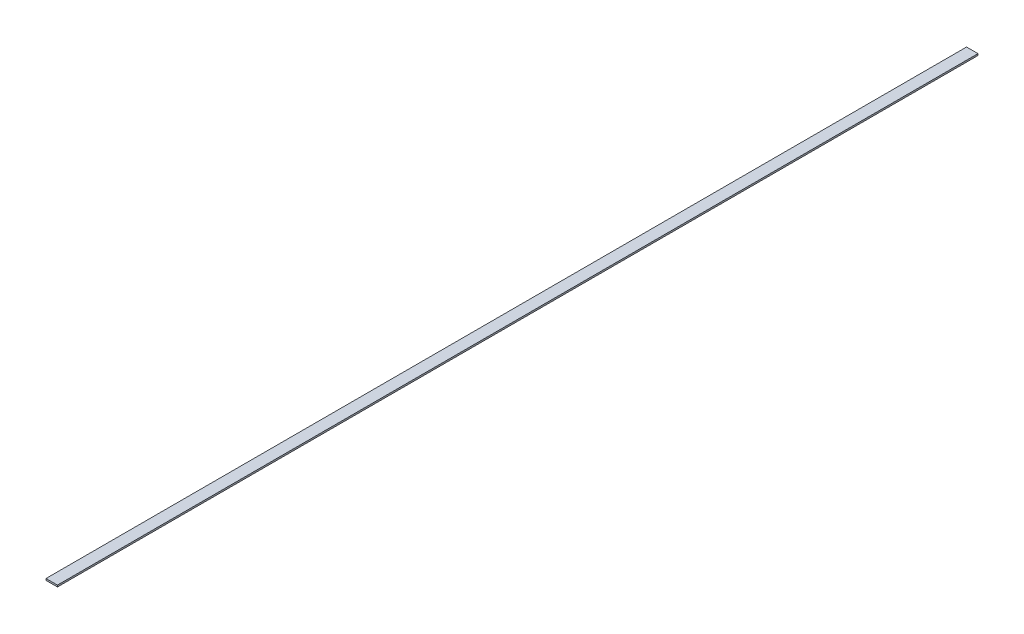
SolidWorks part; units mm, degrees
material "Manual Density from Real Component Bordo attacco e uscita"
ref_plane "Piano frontale" through (0, 0, 0) normal (0, 0, 1) x (1, 0, 0)
ref_plane "Piano superiore" through (0, 0, 0) normal (0, 1, 0) x (1, 0, 0)
ref_plane "Piano destro" through (0, 0, 0) normal (1, 0, 0) x (0, 0, -1)
sketch "Schizzo1" plane through (0, 0, 0) normal (0, 0, 1) x (1, 0, 0)
  line L1 (4.1, -0.6) -> (-4.1, -0.6)
  line L2 (4.1, -0.6) -> (4.1, 0.6)
  line L3 (4.1, 0.6) -> (-4.1, 0.6)
  line L4 (-4.1, -0.6) -> (-4.1, 0.6)
  line L5 (4.1, -0.6) -> (-4.1, 0.6) construction
  line L6 (4.1, 0.6) -> (-4.1, -0.6) construction
  point P0 (0, 0)
  dimension "D1" = 1.2
  dimension "D2" = 8.2
extrude "Estrusione-Estrusione1" add sketch "Schizzo1" along normal blind 660
